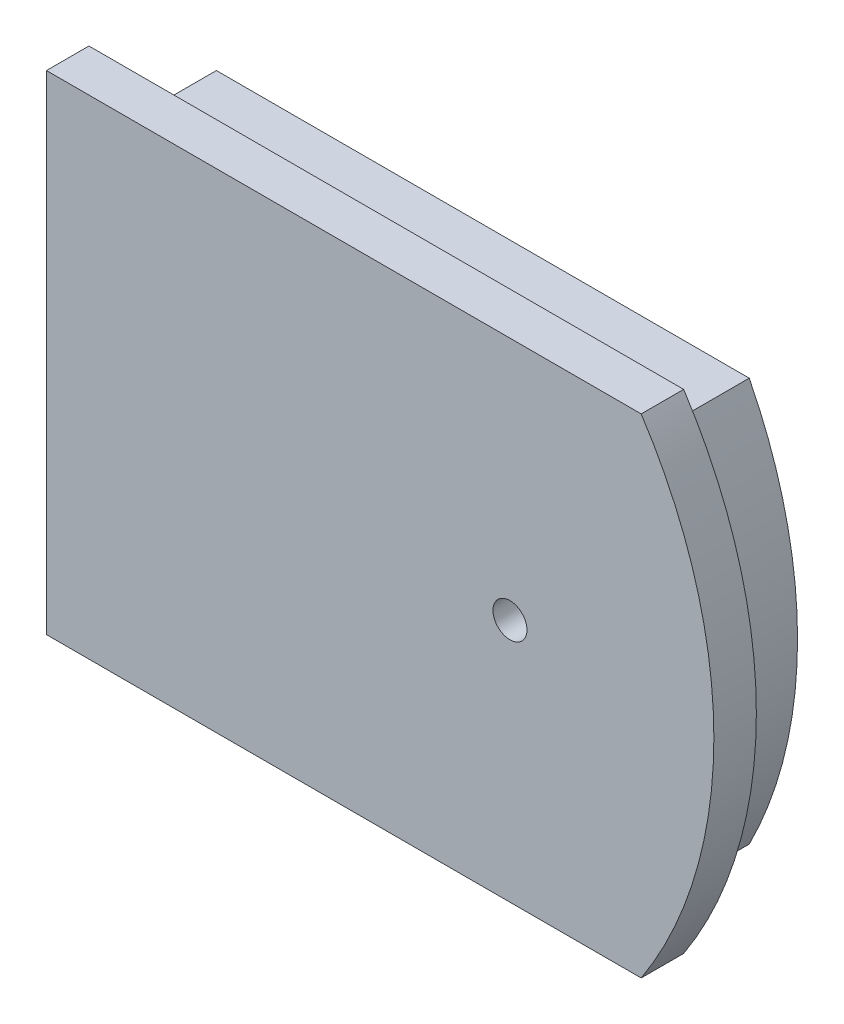
SolidWorks part; units mm, degrees
ref_plane "前视基准面" through (0, 0, 0) normal (0, 0, 1) x (1, 0, 0)
ref_plane "上视基准面" through (0, 0, 0) normal (0, 1, 0) x (1, 0, 0)
ref_plane "右视基准面" through (0, 0, 0) normal (1, 0, 0) x (0, 0, -1)
other "Configuration Table"
sketch "草图1" plane through (0, 0, 0) normal (0, 0, 1) x (1, 0, 0)
  line L0 (0, 0) -> (50000, 0) construction
  line L1 (0, 0) -> (0, 50000) construction
  line L3 (-70, 57.5) -> (70, 57.5)
  line L4 (-70, 57.5) -> (-70, -57.5)
  line L5 (-70, -57.5) -> (70, -57.5)
  line L6 (70, 57.5) -> (70, -57.5)
  dimension "D1" = 140
  dimension "D2" = 115
extrude "凸台-拉伸1" add sketch "草图1" along normal blind 10 contours L4 L3 L6 L5
sketch "草图2" plane through (0, 0, 10) normal (0, 0, 1) x (1, 0, 0)
  line L0 (0, 0) -> (50000, 0) construction
  line L1 (0, 0) -> (0, 50000) construction
  line L2 (70, 57.5) -> (70, -57.5)
  circle A0 centre (-18.0676, 0) radius 105.1768
extrude "凸台-拉伸3" add sketch "草图2" against normal blind 10 contours L1 A0
sketch "草图3" plane through (0, 0, 10) normal (0, 0, 1) x (1, 0, 0)
  line L0 (0, 0) -> (50000, 0) construction
  line L1 (0, 0) -> (0, 50000) construction
  line L2 (87.1092, 0) -> (87.1092, 50000)
  circle A0 centre (37.1092, 0) radius 35
  arc A1 (70, -57.5) -> (70, 57.5) centre (-18.0676, 0) ccw construction
  point P12 (87.1092, 0)
  dimension "D1" = 50
extrude "切除-拉伸2" cut sketch "草图3" against normal blind 10
sketch "草图4" plane through (0, 0, 10) normal (0, 0, 1) x (1, 0, 0)
  circle A0 centre (37.1092, 0) radius 35
extrude "凸台-拉伸4" add sketch "草图4" against normal blind 10
sketch "草图5" plane through (0, 0, 10) normal (0, 0, 1) x (1, 0, 0)
  line L0 (0, 0) -> (50000, 0) construction
  line L1 (0, 0) -> (0, 50000) construction
  line L2 (87.1092, 0) -> (87.1092, 21.6068)
  circle A0 centre (39.1092, 0) radius 4
  arc A1 (70, -57.5) -> (70, 57.5) centre (-18.0676, 0) ccw construction
  dimension "D1" = 48
extrude "切除-拉伸3" cut sketch "草图5" against normal through all contours A0
sketch "草图6" plane through (0, 0, 0) normal (0, 0, -1) x (-1, 0, 0)
  line L0 (0, 0) -> (50000, 0) construction
  line L1 (60, 47.5) -> (-65.4318, 47.5)
  line L2 (60, 47.5) -> (60, -47.5)
  line L3 (60, -47.5) -> (-65.4318, -47.5)
  line L4 (-65.4318, 47.5) -> (-65.4318, -47.5)
  line L5 (0, 0) -> (0, 50000) construction
  line L6 (70, 57.5) -> (-70, 57.5) construction
  line L7 (70, 57.5) -> (70, -57.5) construction
  circle A0 centre (28.0676, 0) radius 105.18
  arc A1 (-70, 57.5) -> (-70, -57.5) centre (18.0676, 0) ccw construction
  point P11 (27.4526, 0)
  point P16 (24.4896, 0)
  point P17 (22.9437, 0)
  point P18 (0, 0)
  point P19 (0, 0)
  point P20 (24.6184, 0)
  dimension "D1" = 10
  dimension "D3" = 10
  dimension "D2" = 10
extrude "凸台-拉伸5" add sketch "草图6" along normal blind 20 contours L2 L1 L4 L3
sketch "草图7" plane through (0, 0, -20) normal (0, 0, -1) x (-1, 0, 0)
  line L0 (0, 0) -> (50000, 0) construction
  line L1 (0, 0) -> (0, 50000) construction
  line L2 (-65.4318, 47.5) -> (-65.4318, -47.5)
  circle A0 centre (28.0676, 0) radius 104.8732
  arc A1 (-70, 57.5) -> (-70, -57.5) centre (18.0676, 0) ccw construction
  line M5 (-65.4318, 47.5) -> (-65.4318, -47.5)
  dimension "D1" = 10
extrude "凸台-拉伸6" add sketch "草图7" against normal blind 20 contours A0 M5
sketch "草图8" plane through (0, 0, 0) normal (0, 0, 1) x (1, 0, 0)
  circle A0 centre (39.1092, 0) radius 4
extrude "切除-拉伸5" cut sketch "草图8" against normal through all
